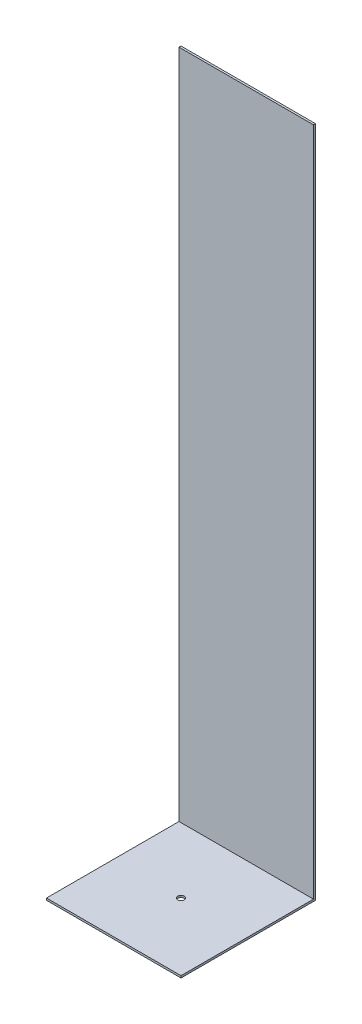
SolidWorks part; units mm, degrees
ref_plane "Front Plane" through (0, 0, 0) normal (0, 0, 1) x (1, 0, 0)
ref_plane "Top Plane" through (0, 0, 0) normal (0, 1, 0) x (1, 0, 0)
ref_plane "Right Plane" through (0, 0, 0) normal (1, 0, 0) x (0, 0, -1)
sketch "Sketch1" plane through (0, 0, 0) normal (1, 0, 0) x (0, 0, -1)
  line L0 (0, 500) -> (0, -500)
  line L1 (0, -500) -> (-200, -500)
  point P4 (0, 0)
  dimension "D1" = 1000
  dimension "D2" = 200
extrude "Extrude-Thin1" add sketch "Sketch1" against normal blind 200 thin
sketch "Sketch2" plane through (0, -500, 0) normal (0, -1, 0) x (1, 0, 0)
  line L0 (-100, 200) -> (-100, 0) construction
  line L1 (-200, 200) -> (0, 200) construction
  line L2 (-200, 0) -> (0, 0) construction
  line L3 (-200, 100) -> (0, 100) construction
  line L4 (-200, 0) -> (-200, 200) construction
  line L5 (0, 0) -> (0, 200) construction
  circle A0 centre (-100, 100) radius 5
  dimension "D1" = 10
extrude "Cut-Extrude1" cut sketch "Sketch2" against normal blind 10
